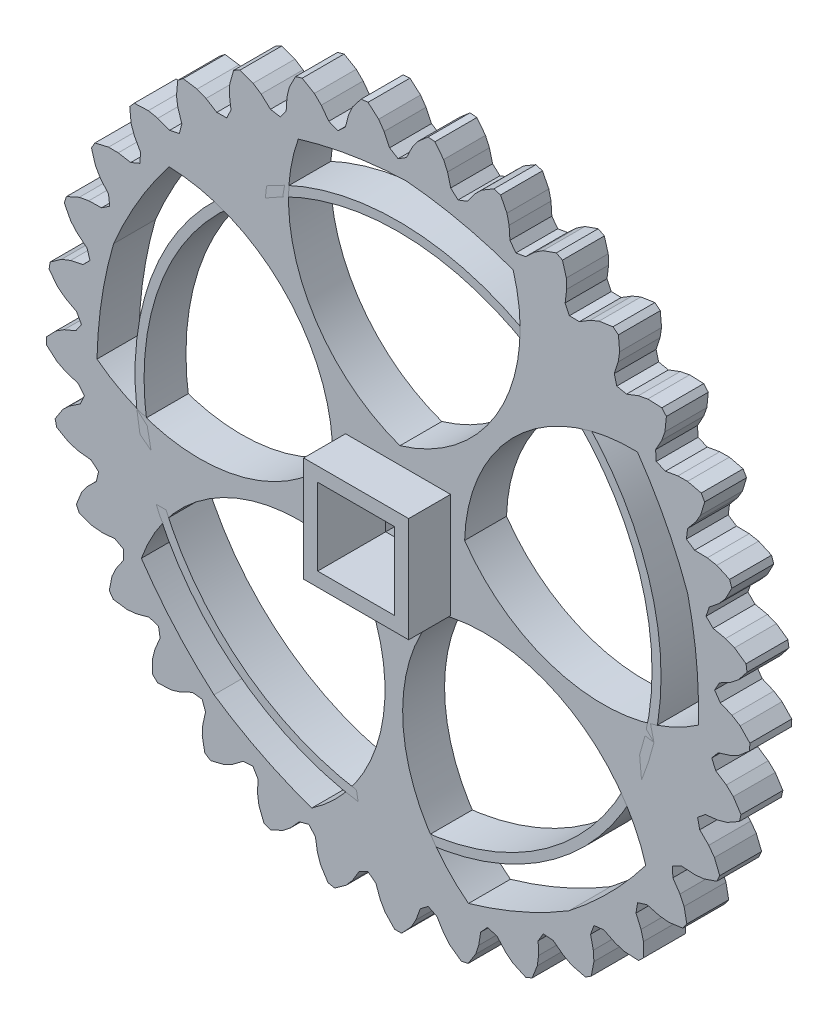
SolidWorks part; units mm, degrees
ref_plane "Front Plane" through (0, 0, 0) normal (0, 0, 1) x (1, 0, 0)
ref_plane "Top Plane" through (0, 0, 0) normal (0, 1, 0) x (1, 0, 0)
ref_plane "Right Plane" through (0, 0, 0) normal (1, 0, 0) x (0, 0, -1)
sketch "Sketch1" plane through (0, 0, 0) normal (0, 0, 1) x (1, 0, 0)
  line L1 (3.675, -3.675) -> (-3.675, -3.675)
  line L2 (3.675, -3.675) -> (3.675, 3.675)
  line L3 (3.675, 3.675) -> (-3.675, 3.675)
  line L4 (-3.675, -3.675) -> (-3.675, 3.675)
  circle A0 centre (0, 0) radius 33.6129
  point P3 (0, 3.675)
  point P9 (-3.675, 0)
  dimension "D1" = 67.2257
  dimension "D2" = 7.35
  dimension "D3" = 7.35
extrude "Boss-Extrude1" add sketch "Sketch1" along normal blind 4
sketch "Sketch2" plane through (0, 0, 0) normal (0, 0, 1) x (1, 0, 0)
  line L0 (0, 0) -> (0, 34.8589) construction
  line L1 (0, 30.2608) -> (-0.8069, 30.7591)
  line L2 (-0.8069, 30.7591) -> (-1.33, 31.849)
  line L3 (-1.33, 31.849) -> (-1.8557, 32.6046)
  line L4 (-1.8557, 32.6046) -> (-2.8665, 33.4904)
  line L5 (-2.8665, 33.4904) -> (-1.8557, 34.2629)
  line L6 (-1.8557, 34.2629) -> (0, 34.8589)
  line L7 (1.8557, 34.2629) -> (0, 34.8589)
  line L8 (2.8665, 33.4904) -> (1.8557, 34.2629)
  line L9 (1.8557, 32.6046) -> (2.8665, 33.4904)
  line L10 (1.33, 31.849) -> (1.8557, 32.6046)
  line L11 (0.8069, 30.7591) -> (1.33, 31.849)
  line L12 (0, 30.2608) -> (0.8069, 30.7591)
  circle A22 centre (0, 0) radius 33.6129 construction
  dimension "D5" = 0.5258
  dimension "D6" = 0.7556
  dimension "D9" = 0.5959
  dimension "D1" = 0.8069
  dimension "D2" = 0.4984
  dimension "D3" = 0.5231
  dimension "D4" = 1.0898
  dimension "D7" = 0.8858
  dimension "D8" = 1.8557
  dimension "D10" = 1.0107
  dimension "D11" = 0.7725
  dimension "D12" = 1.0107
extrude "Cut-Extrude1" cut sketch "Sketch2" along normal through all
pattern_circular "CirPattern1" count 33 over 360 about axis through (0, 0, 0) along (0, 0, 1) of "Cut-Extrude1"
sketch "Sketch3" plane through (0, 0, 0) normal (0, 0, 1) x (1, 0, 0)
  circle A0 centre (0, 0) radius 29.75
  dimension "D1" = 59.5
sketch "Sketch4" plane through (0, 0, 0) normal (0, 0, 1) x (1, 0, 0)
  line L0 (0, 0) -> (0.7854, 28.8152) construction
  arc A1 (0.7854, 28.8152) -> (-9.5267, 27.1273) centre (2.0438, -11.2177) ccw
  arc A2 (0.7854, 28.8152) -> (10.9903, 26.5681) centre (-2.6519, -11.0897) cw
  arc A4 (0.1805, 6.623) -> (-9.5267, 27.1273) centre (5.5791, 21.7288) cw
  arc A5 (0.1805, 6.623) -> (10.9903, 26.5681) centre (-4.3872, 22.0004) ccw
extrude "Cut-Extrude2" cut sketch "Sketch4" along normal through all both
sketch "Sketch5" plane through (0, 0, 0) normal (0, 0, 1) x (1, 0, 0)
  circle A0 centre (0, 0) radius 25.1098
  circle A1 centre (0, 0) radius 24.2496
extrude "Boss-Extrude2" add sketch "Sketch5" along normal through all separate body
pattern_circular "CirPattern2" count 5 over 360 about axis through (0, 0, 0) along (0, 0, 1) of "Cut-Extrude2"
chamfer "Chamfer1" distance 1.5 distance2 0.5 4 edges at (-3.675, 0, 0) (0, -3.675, 0) (3.675, 0, 0) (0, 3.675, 0)
sketch "Sketch6" plane through (0, 0, 4) normal (0, 0, 1) x (1, 0, 0)
  line L1 (-3.675, 3.675) -> (3.675, 3.675)
  line L2 (-3.675, 3.675) -> (-3.675, -3.675)
  line L3 (-3.675, -3.675) -> (3.675, -3.675)
  line L4 (3.675, 3.675) -> (3.675, -3.675)
  line L5 (-5.0131, 5.0131) -> (5.0131, 5.0131)
  line L6 (-5.0131, 5.0131) -> (-5.0131, -5.0131)
  line L7 (-5.0131, -5.0131) -> (5.0131, -5.0131)
  line L8 (5.0131, 5.0131) -> (5.0131, -5.0131)
  dimension "D1" = 1.3381
  dimension "D2" = 1.3381
  dimension "D3" = 1.3381
  dimension "D4" = 1.3381
extrude "Boss-Extrude3" add sketch "Sketch6" along normal blind 4
equation "\"padding\"=1.33807"
equation "\"D1@Sketch6\"=\"padding\""
equation "\"D2@Sketch6\"=\"padding\""
equation "\"D3@Sketch6\"=\"padding\""
equation "\"D4@Sketch6\"=\"padding\""
